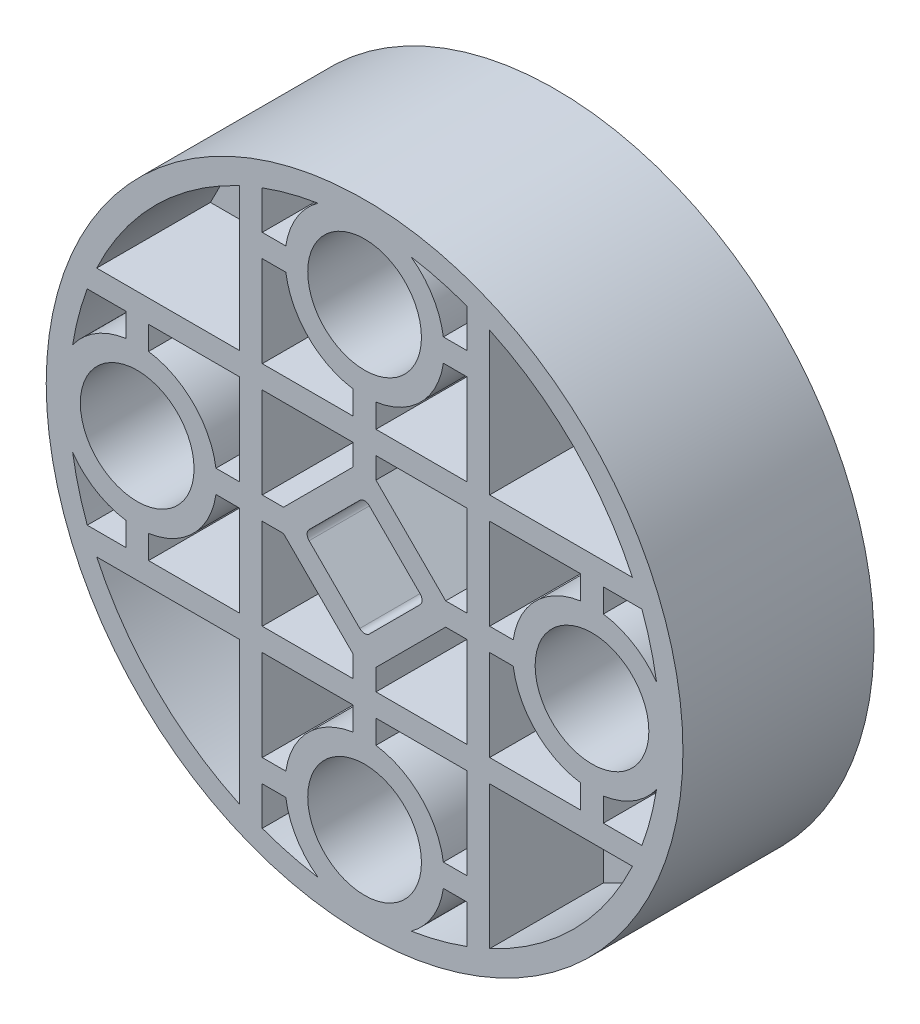
SolidWorks part; units mm, degrees
ref_plane "Front Plane" through (0, 0, 0) normal (0, 0, 1) x (1, 0, 0)
ref_plane "Top Plane" through (0, 0, 0) normal (0, 1, 0) x (1, 0, 0)
ref_plane "Right Plane" through (0, 0, 0) normal (1, 0, 0) x (0, 0, -1)
sketch "Sketch1" plane through (0, 0, 0) normal (0, 0, 1) x (1, 0, 0)
  line L0 (-22.0244, -11.2) -> (5.9756, -11.2) construction
  line L1 (-8.0244, -25.2) -> (-8.0244, 2.8) construction
  circle A0 centre (-8.0244, -11.2) radius 14 construction
  circle A1 centre (-8.0244, -11.2) radius 14
  circle A2 centre (-18.0244, -11.2) radius 2.5 construction
  circle A3 centre (-18.0244, -11.2) radius 2.5
  circle A4 centre (-8.0244, -1.2) radius 2.5 construction
  circle A5 centre (-8.0244, -1.2) radius 2.5
  circle A8 centre (-8.0244, -21.2) radius 2.5 construction
  circle A9 centre (1.9756, -11.2) radius 2.5 construction
  circle A10 centre (-8.0244, -21.2) radius 2.5
  circle A11 centre (1.9756, -11.2) radius 2.5
extrude "Boss-Extrude1" add sketch "Sketch1" along normal up to vertex (9.2 mm away)
sketch "Sketch2" plane through (0, 0, 9.2) normal (0, 0, 1) x (1, 0, 0)
  line L0 (-9.9744, -12.9197) -> (-9.9744, -9.4803)
  line L2 (-6.0744, -12.9197) -> (-6.0744, -9.4803)
  circle A0 centre (-8.0244, -11.2) radius 2.6
  dimension "D1" = 5.2
  dimension "D2" = 3.9
extrude "Cut-Extrude1" cut sketch "Sketch2" against normal through all contours L2 A0 L0
sketch "Sketch3" plane through (0, 0, 9.2) normal (0, 0, 1) x (1, 0, 0)
  line L0 (-12.5244, -23.2) -> (-12.5244, -23.3963)
  line L1 (-20.0244, -6.7) -> (-20.2207, -6.7)
  line L2 (-13.0244, 0.8) -> (-13.0244, -23.2) construction
  line L3 (-3.0244, -23.2) -> (-3.0244, 0.8) construction
  line L4 (-4.0744, -13.5574) -> (-4.0744, -8.8426)
  line L5 (-11.9744, -8.8426) -> (-11.9744, -13.5574)
  line L6 (-4.0744, -13.5574) -> (-4.0744, -8.8426)
  line L7 (-11.9744, -8.8426) -> (-11.9744, -13.5574)
  line L8 (-8.0244, -11.2) -> (-8.0244, 2.8) construction
  line L9 (-13.5244, 0.5792) -> (-13.5244, -22.9792)
  line L10 (-12.5244, 0.9963) -> (-12.5244, -23.2)
  line L11 (-2.5244, -22.9792) -> (-2.5244, 0.5792)
  line L12 (-3.5244, -23.3963) -> (-3.5244, 0.9963)
  line L13 (-3.5244, -23.2) -> (-3.5244, 0.8) construction
  line L14 (-2.5244, -23.2) -> (-2.5244, 0.8) construction
  line L15 (-12.5244, 0.8) -> (-12.5244, -23.2) construction
  line L16 (-13.5244, 0.8) -> (-13.5244, -23.2) construction
  line L17 (4.1719, -6.7) -> (-20.0244, -6.7)
  line L18 (3.7548, -5.7) -> (-19.8036, -5.7)
  line L19 (-20.2207, -15.7) -> (4.1719, -15.7)
  line L20 (-19.8036, -16.7) -> (3.7548, -16.7)
  line L21 (-8.0244, -11.2) -> (-12.5244, -23.2) construction
  line L22 (-8.0244, -11.2) -> (-20.0244, -6.7) construction
  circle A2 centre (-18.0244, -11.2) radius 3.5
  circle A3 centre (-18.0244, -11.2) radius 3.5
  circle A19 centre (-8.0244, -21.2) radius 3.5
  circle A20 centre (-8.0244, -21.2) radius 3.5
  circle A22 centre (1.9756, -11.2) radius 3.5
  circle A23 centre (1.9756, -11.2) radius 3.5
  circle A25 centre (-8.0244, -1.2) radius 3.5
  circle A26 centre (-8.0244, -1.2) radius 3.5
  circle A28 centre (-8.0244, -11.2) radius 13
  circle A29 centre (-8.0244, -11.2) radius 13
  arc A34 (-11.9744, -13.5574) -> (-4.0744, -13.5574) centre (-8.0244, -11.2) ccw
  arc A35 (-4.0744, -8.8426) -> (-11.9744, -8.8426) centre (-8.0244, -11.2) ccw
  arc A36 (-11.9744, -13.5574) -> (-4.0744, -13.5574) centre (-8.0244, -11.2) ccw
  arc A37 (-4.0744, -8.8426) -> (-11.9744, -8.8426) centre (-8.0244, -11.2) ccw
  dimension "D7" = 5
  dimension "D8" = 5
  dimension "D13" = 2
  dimension "D14" = 90
  dimension "D1" = 1
  dimension "D2" = 1
  dimension "D3" = 1
  dimension "D4" = 1
  dimension "D5" = 1
  dimension "D6" = 2
  dimension "D9" = 0.5
  dimension "D10" = 0.5
  dimension "D11" = 0.5
  dimension "D12" = 0.5
extrude "Cut-Extrude2" cut sketch "Sketch3" against normal blind 5 contours L9 A29 L18 | L12 A29 A26 L10 L18 | L1 A29 A3 L19 L9 L17 | A37 L17 L10 L19 A36 L7 | A37 L6 A36 L19 L12 L17 | A23 A29 L17 L11 L19 | L18 A29 L11 | L11 A29 L20 | L0 A29 A20 L12 L20 L10 | L20 A29 L9
sketch "Sketch4" plane through (0, 0, 0) normal (0, 0, -1) x (-1, 0, 0)
  circle A2 centre (8.0244, -11.2) radius 13
  circle A3 centre (8.0244, -11.2) radius 13
  dimension "D1" = 1
extrude "Cut-Extrude3" cut sketch "Sketch4" against normal blind 0.8
sketch "Sketch5" plane through (0, 0, 0.8) normal (0, 0, -1) x (-1, 0, 0)
  line L0 (8.0244, 2.8) -> (8.0244, -25.2) construction
  circle A0 centre (8.0244, -11.2) radius 4.25
  dimension "D1" = 8.5
extrude "Cut-Extrude4" cut sketch "Sketch5" against normal offset from surface (0.7 mm away) 1.5 up to face at (-21.0244, -11.2, 0)
sketch "Sketch6" plane through (0, 0, 0.8) normal (0, 0, -1) x (-1, 0, 0)
  circle A0 centre (8.0244, -11.2) radius 4.25 construction
  circle A1 centre (8.0244, -11.2) radius 4.25
  circle A2 centre (8.0244, -11.2) radius 5.25
  dimension "D1" = 1
extrude "Boss-Extrude2" add sketch "Sketch6" along normal up to surface (0.8 mm away) up to face at (-21.0244, -11.2, 0)
sketch "Sketch7" plane through (0, 0, 0.8) normal (0, 0, -1) x (-1, 0, 0)
  line L0 (7.0705, -15.7) -> (3.5244, -15.7) construction
  line L1 (3.5244, -6.7) -> (7.0705, -6.7) construction
  line L2 (3.5244, -5.7) -> (12.5244, -5.7) construction
  line L3 (12.5244, -16.7) -> (3.5244, -16.7) construction
  line L4 (-3.7548, -5.7) -> (2.5244, -5.7) construction
  line L5 (-4.1719, -6.7) -> (2.5244, -6.7) construction
  line L6 (2.5244, -15.7) -> (-4.1719, -15.7) construction
  line L7 (2.5244, -16.7) -> (-3.7548, -16.7) construction
  line L8 (2.5244, -22.9792) -> (2.5244, -16.7) construction
  line L9 (3.5244, -23.3963) -> (3.5244, -16.7) construction
  line L10 (2.5244, -15.7) -> (2.5244, -6.7) construction
  line L11 (2.5244, -5.7) -> (2.5244, 0.5792) construction
  line L12 (3.5244, -5.7) -> (3.5244, 0.9963) construction
  line L13 (3.5244, -15.7) -> (3.5244, -6.7) construction
  line L14 (12.5244, -16.7) -> (12.5244, -23.3963) construction
  line L15 (12.5244, 0.9963) -> (12.5244, -5.7) construction
  line L16 (12.5244, -6.7) -> (12.5244, -15.7) construction
  line L17 (13.5244, -16.7) -> (13.5244, -22.9792) construction
  line L18 (13.5244, 0.5792) -> (13.5244, -5.7) construction
  line L19 (13.5244, -5.7) -> (19.8036, -5.7) construction
  line L20 (13.5244, -6.7) -> (20.2207, -6.7) construction
  line L21 (13.5244, -6.7) -> (13.5244, -15.7) construction
  line L22 (20.2207, -15.7) -> (13.5244, -15.7) construction
  line L23 (19.8036, -16.7) -> (13.5244, -16.7) construction
  line L24 (12.5244, -15.7) -> (3.5244, -15.7)
  line L25 (3.5244, -6.7) -> (12.5244, -6.7)
  line L26 (3.5244, -5.7) -> (12.5244, -5.7)
  line L27 (12.5244, -16.7) -> (3.5244, -16.7)
  line L28 (-3.7548, -5.7) -> (2.5244, -5.7)
  line L29 (-4.1719, -6.7) -> (2.5244, -6.7)
  line L30 (2.5244, -15.7) -> (-4.1719, -15.7)
  line L31 (2.5244, -16.7) -> (-3.7548, -16.7)
  line L32 (2.5244, -22.9792) -> (2.5244, -16.7)
  line L33 (3.5244, -23.3963) -> (3.5244, -16.7)
  line L34 (2.5244, -15.7) -> (2.5244, -6.7)
  line L35 (2.5244, -5.7) -> (2.5244, 0.5792)
  line L36 (3.5244, -5.7) -> (3.5244, 0.9963)
  line L37 (3.5244, -15.7) -> (3.5244, -6.7)
  line L38 (12.5244, -16.7) -> (12.5244, -23.3963)
  line L39 (12.5244, 0.9963) -> (12.5244, -5.7)
  line L40 (12.5244, -6.7) -> (12.5244, -15.7)
  line L41 (13.5244, -16.7) -> (13.5244, -22.9792)
  line L42 (13.5244, 0.5792) -> (13.5244, -5.7)
  line L43 (13.5244, -5.7) -> (19.8036, -5.7)
  line L44 (13.5244, -6.7) -> (20.2207, -6.7)
  line L45 (13.5244, -6.7) -> (13.5244, -15.7)
  line L46 (20.2207, -15.7) -> (13.5244, -15.7)
  line L47 (19.8036, -16.7) -> (13.5244, -16.7)
  circle A2 centre (18.0244, -11.2) radius 3.5
  circle A3 centre (18.0244, -11.2) radius 3.5
  circle A5 centre (8.0244, -1.2) radius 3.5
  circle A6 centre (8.0244, -1.2) radius 3.5
  circle A8 centre (-1.9756, -11.2) radius 3.5
  circle A9 centre (-1.9756, -11.2) radius 3.5
  circle A10 centre (8.0244, -11.2) radius 13 construction
  circle A11 centre (8.0244, -21.2) radius 3.5
  circle A12 centre (8.0244, -21.2) radius 3.5
  circle A13 centre (8.0244, -11.2) radius 13
  circle A14 centre (8.0244, -11.2) radius 5.25 construction
  circle A15 centre (8.0244, -11.2) radius 5.25
  circle A17 centre (8.0244, -11.2) radius 14
  circle A18 centre (8.0244, -11.2) radius 14
  circle M6 centre (8.0244, -11.2) radius 13
  circle M11 centre (8.0244, -11.2) radius 5.25
  dimension "D1" = 1
  dimension "D2" = 1
  dimension "D3" = 1
  dimension "D4" = 1
  dimension "D5" = 0
extrude "Cut-Extrude5" cut sketch "Sketch7" against normal offset from surface (2.4 mm away) 1 contours L28 L35 M6 | A9 L30 L34 L29 M6 | L32 L31 M6 | A12 L38 L27 L33 M6 | A6 L36 L26 L39 M6 | L42 L43 M6 | A3 L44 L45 L46 M6 | L47 L41 M6 | L40 L24 M11 | L40 L25 M11 | L37 L25 M11 | L37 L24 M11 up to face at (-0.2471, -18.9773, 4.2)
chamfer "Chamfer1" distance 0.6 angle 45 4 edges at (-6.0744, -11.2, 1.5) (-8.0244, -8.6, 1.5) (-8.0244, -13.8, 1.5) (-9.9744, -11.2, 1.5)
sketch "Sketch8" plane through (0, 0, 9.2) normal (0, 0, 1) x (1, 0, 0)
  line L0 (-11.9744, -8.8426) -> (-11.9744, -13.5574) construction
  line L1 (-11.9744, -8.8426) -> (-11.9744, -13.5574)
  line L2 (-4.0744, -13.5574) -> (-4.0744, -8.8426) construction
  line L3 (-4.0744, -13.5574) -> (-4.0744, -8.8426)
  line L4 (-8.0244, -7.1341) -> (-12.0903, -11.2)
  line L5 (-3.9586, -11.2) -> (-8.0244, -7.1341)
  line L6 (-8.0244, -15.2659) -> (-3.9586, -11.2)
  line L7 (-12.0903, -11.2) -> (-8.0244, -15.2659)
  line L8 (-8.0244, -7.1341) -> (-12.0903, -11.2)
  line L9 (-3.9586, -11.2) -> (-8.0244, -7.1341)
  line L10 (-8.0244, -15.2659) -> (-3.9586, -11.2)
  line L11 (-12.0903, -11.2) -> (-8.0244, -15.2659)
  line L12 (-8.0244, -13.8517) -> (-5.3728, -11.2)
  line L13 (-10.6761, -11.2) -> (-8.0244, -13.8517)
  line L14 (-8.0244, -8.5483) -> (-10.6761, -11.2)
  line L15 (-5.3728, -11.2) -> (-8.0244, -8.5483)
  line L16 (-8.0244, -13.8517) -> (-5.3728, -11.2)
  line L17 (-10.6761, -11.2) -> (-8.0244, -13.8517)
  line L18 (-8.0244, -8.5483) -> (-10.6761, -11.2)
  line L19 (-5.3728, -11.2) -> (-8.0244, -8.5483)
  line L20 (-3.5244, -6.7) -> (-12.5244, -6.7)
  line L21 (-3.5244, -15.7) -> (-3.5244, -6.7)
  line L22 (-12.5244, -15.7) -> (-3.5244, -15.7)
  line L23 (-12.5244, -6.7) -> (-12.5244, -15.7)
  line L24 (-3.5244, -6.7) -> (-12.5244, -6.7)
  line L25 (-3.5244, -15.7) -> (-3.5244, -6.7)
  line L26 (-12.5244, -15.7) -> (-3.5244, -15.7)
  line L27 (-12.5244, -6.7) -> (-12.5244, -15.7)
  dimension "D1" = 0
  dimension "D2" = 0
  dimension "D3" = 0
extrude "Cut-Extrude6" cut sketch "Sketch8" against normal up to surface (5 mm away)
sketch "Sketch9" plane through (0, 0, 9.2) normal (0, 0, 1) x (1, 0, 0)
  line L0 (-4.0744, -13.5574) -> (-4.0744, -8.8426) construction
  line L1 (-11.9744, -8.8426) -> (-11.9744, -13.5574) construction
  line L2 (-4.0744, -13.5574) -> (-4.0744, -8.8426)
  line L3 (-11.9744, -8.8426) -> (-11.9744, -13.5574)
  line L4 (-3.5244, -6.7) -> (-12.5244, -6.7)
  line L5 (-12.5244, -6.7) -> (-12.5244, -15.7)
  line L6 (-12.5244, -15.7) -> (-3.5244, -15.7)
  line L7 (-3.5244, -15.7) -> (-3.5244, -6.7)
  line L8 (-3.5244, -6.7) -> (-12.5244, -6.7)
  line L9 (-12.5244, -6.7) -> (-12.5244, -15.7)
  line L10 (-12.5244, -15.7) -> (-3.5244, -15.7)
  line L11 (-3.5244, -15.7) -> (-3.5244, -6.7)
  line L12 (-8.0244, -13.8517) -> (-5.3728, -11.2)
  line L13 (-5.3728, -11.2) -> (-8.0244, -8.5483)
  line L14 (-8.0244, -8.5483) -> (-10.6761, -11.2)
  line L15 (-10.6761, -11.2) -> (-8.0244, -13.8517)
  line L16 (-8.0244, -13.8517) -> (-5.3728, -11.2)
  line L17 (-5.3728, -11.2) -> (-8.0244, -8.5483)
  line L18 (-8.0244, -8.5483) -> (-10.6761, -11.2)
  line L19 (-10.6761, -11.2) -> (-8.0244, -13.8517)
  line L20 (-8.0244, -7.1341) -> (-12.0903, -11.2)
  line L21 (-12.0903, -11.2) -> (-8.0244, -15.2659)
  line L22 (-8.0244, -15.2659) -> (-3.9586, -11.2)
  line L23 (-3.9586, -11.2) -> (-8.0244, -7.1341)
  line L24 (-8.0244, -7.1341) -> (-12.0903, -11.2)
  line L25 (-12.0903, -11.2) -> (-8.0244, -15.2659)
  line L26 (-8.0244, -15.2659) -> (-3.9586, -11.2)
  line L27 (-3.9586, -11.2) -> (-8.0244, -7.1341)
  line M18 (-11.9744, -11.0841) -> (-11.9744, -11.3159)
  line M21 (-4.0744, -11.3159) -> (-4.0744, -11.0841)
  dimension "D1" = 0
  dimension "D2" = 0
  dimension "D3" = 0
extrude "Boss-Extrude3" add sketch "Sketch9" against normal up to surface (5 mm away) contours L24 L25 M18 | L26 L27 M21 up to face at (-8.0244, -11.2, 4.2)
sketch "Sketch10" plane through (0, 0, 9.2) normal (0, 0, 1) x (1, 0, 0)
  line L4 (-8.0244, -7.1341) -> (-12.0903, -11.2)
  line L5 (-12.0903, -11.2) -> (-8.0244, -15.2659)
  line L6 (-8.0244, -15.2659) -> (-3.9586, -11.2)
  line L7 (-3.9586, -11.2) -> (-8.0244, -7.1341)
  line L8 (-8.0244, -7.1341) -> (-12.0903, -11.2)
  line L9 (-12.0903, -11.2) -> (-8.0244, -15.2659)
  line L10 (-8.0244, -15.2659) -> (-3.9586, -11.2)
  line L11 (-3.9586, -11.2) -> (-8.0244, -7.1341)
  dimension "D1" = 0
extrude "Boss-Extrude4" add sketch "Sketch10" against normal up to surface (0.2 mm away)
sketch "Sketch11" plane through (0, 0, 9.2) normal (0, 0, 1) x (1, 0, 0)
  line L0 (-11.9744, -8.8426) -> (-11.9744, -13.5574) construction
  line L1 (-4.0744, -13.5574) -> (-4.0744, -8.8426) construction
  line L2 (-11.9744, -8.8426) -> (-11.9744, -13.5574)
  line L3 (-4.0744, -13.5574) -> (-4.0744, -8.8426)
  line L4 (-8.0244, -7.1341) -> (-12.0903, -11.2)
  line L5 (-12.0903, -11.2) -> (-8.0244, -15.2659)
  line L6 (-8.0244, -15.2659) -> (-3.9586, -11.2)
  line L7 (-3.9586, -11.2) -> (-8.0244, -7.1341)
  line L8 (-8.0244, -7.1341) -> (-12.0903, -11.2)
  line L9 (-12.0903, -11.2) -> (-8.0244, -15.2659)
  line L10 (-8.0244, -15.2659) -> (-3.9586, -11.2)
  line L11 (-3.9586, -11.2) -> (-8.0244, -7.1341)
  line L12 (-8.0244, -13.8517) -> (-5.3728, -11.2)
  line L13 (-5.3728, -11.2) -> (-8.0244, -8.5483)
  line L14 (-8.0244, -8.5483) -> (-10.6761, -11.2)
  line L15 (-10.6761, -11.2) -> (-8.0244, -13.8517)
  line L16 (-8.0244, -13.8517) -> (-5.3728, -11.2)
  line L17 (-5.3728, -11.2) -> (-8.0244, -8.5483)
  line L18 (-8.0244, -8.5483) -> (-10.6761, -11.2)
  line L19 (-10.6761, -11.2) -> (-8.0244, -13.8517)
  line L20 (-3.5244, -6.7) -> (-12.5244, -6.7)
  line L21 (-12.5244, -6.7) -> (-12.5244, -15.7)
  line L22 (-12.5244, -15.7) -> (-3.5244, -15.7)
  line L23 (-3.5244, -15.7) -> (-3.5244, -6.7)
  line L24 (-3.5244, -6.7) -> (-12.5244, -6.7)
  line L25 (-12.5244, -6.7) -> (-12.5244, -15.7)
  line L26 (-12.5244, -15.7) -> (-3.5244, -15.7)
  line L27 (-3.5244, -15.7) -> (-3.5244, -6.7)
  dimension "D1" = 0
  dimension "D2" = 0
  dimension "D3" = 0
extrude "Cut-Extrude7" cut sketch "Sketch11" against normal up to surface (0.2 mm away) contours L18 L19 L16 L17 up to face at (-8.0244, -11.2, 9)
fillet "Fillet1" [suppressed] radius 0.2
sketch "Sketch12" plane through (0, 0, 9.2) normal (0, 0, 1) x (1, 0, 0)
  line L4 (-12.0903, -11.2) -> (-8.0244, -15.2659)
  line L5 (-8.0244, -7.1341) -> (-12.0903, -11.2)
  line L6 (-3.9586, -11.2) -> (-8.0244, -7.1341)
  line L7 (-8.0244, -15.2659) -> (-3.9586, -11.2)
  line L8 (-12.0903, -11.2) -> (-8.0244, -15.2659)
  line L9 (-8.0244, -7.1341) -> (-12.0903, -11.2)
  line L10 (-3.9586, -11.2) -> (-8.0244, -7.1341)
  line L11 (-8.0244, -15.2659) -> (-3.9586, -11.2)
  line L12 (-13.1509, -11.2) -> (-8.0244, -16.3265)
  line L13 (-8.0244, -6.0735) -> (-13.1509, -11.2)
  line L14 (-2.8979, -11.2) -> (-8.0244, -6.0735)
  line L15 (-8.0244, -16.3265) -> (-2.8979, -11.2)
  line L16 (-13.1509, -11.2) -> (-8.0244, -16.3265)
  line L17 (-8.0244, -6.0735) -> (-13.1509, -11.2)
  line L18 (-2.8979, -11.2) -> (-8.0244, -6.0735)
  line L19 (-8.0244, -16.3265) -> (-2.8979, -11.2)
  dimension "D1" = 0
  dimension "D2" = 0
extrude "Boss-Extrude5" [suppressed] add sketch "Sketch12" against normal up to surface (5 mm away)
sketch "Sketch13" plane through (0, 0, 9.2) normal (0, 0, 1) x (1, 0, 0)
  line L0 (-20.2207, -15.7) -> (-13.5244, -15.7) construction
  line L1 (-13.5244, -6.7) -> (-13.5244, -15.7) construction
  line L2 (-13.5244, -6.7) -> (-20.2207, -6.7) construction
  line L3 (-12.5244, 0.9963) -> (-12.5244, -5.7) construction
  line L4 (-3.5244, -5.7) -> (-12.5244, -5.7) construction
  line L5 (-3.5244, -5.7) -> (-3.5244, 0.9963) construction
  line L6 (-3.5244, -1.7) -> (-12.5244, -1.7) construction
  line L7 (-8.5244, -1.2) -> (-8.5244, -21.2) construction
  line L8 (-7.5244, -1.2) -> (-7.5244, -21.2) construction
  line L9 (-3.5244, -0.7) -> (-12.5244, -0.7) construction
  line L10 (-3.5244, -20.7) -> (-12.5244, -20.7) construction
  line L11 (-3.5244, -21.7) -> (-12.5244, -21.7) construction
  line L12 (-3.5244, -16.7) -> (-3.5244, -23.3963) construction
  line L13 (-12.5244, -16.7) -> (-3.5244, -16.7) construction
  line L14 (-12.5244, -23.3963) -> (-12.5244, -16.7) construction
  line L15 (-2.5244, -6.7) -> (4.1719, -6.7) construction
  line L16 (-2.5244, -15.7) -> (-2.5244, -6.7) construction
  line L17 (-18.0244, -11.7) -> (1.9756, -11.7) construction
  line L18 (-18.0244, -10.7) -> (1.9756, -10.7) construction
  line L19 (1.4756, -6.7) -> (1.4756, -15.7) construction
  line L20 (2.4756, -6.7) -> (2.4756, -15.7) construction
  line L21 (4.1719, -15.7) -> (-2.5244, -15.7) construction
  line L22 (-18.5244, -6.7) -> (-18.5244, -15.7) construction
  line L23 (-17.5244, -6.7) -> (-17.5244, -15.7) construction
  line L24 (-20.2207, -15.7) -> (-13.5244, -15.7)
  line L25 (-13.5244, -6.7) -> (-13.5244, -15.7)
  line L26 (-13.5244, -6.7) -> (-20.2207, -6.7)
  line L27 (-12.5244, 0.9963) -> (-12.5244, -5.7)
  line L28 (-3.5244, -5.7) -> (-12.5244, -5.7)
  line L29 (-3.5244, -5.7) -> (-3.5244, 0.9963)
  line L30 (-3.5244, -1.7) -> (-12.5244, -1.7)
  line L31 (-8.5244, -1.2) -> (-8.5244, -21.2)
  line L32 (-7.5244, -1.2) -> (-7.5244, -21.2)
  line L33 (-3.5244, -0.7) -> (-12.5244, -0.7)
  line L34 (-3.5244, -20.7) -> (-12.5244, -20.7)
  line L35 (-3.5244, -21.7) -> (-12.5244, -21.7)
  line L36 (-3.5244, -16.7) -> (-3.5244, -23.3963)
  line L37 (-12.5244, -16.7) -> (-3.5244, -16.7)
  line L38 (-12.5244, -23.3963) -> (-12.5244, -16.7)
  line L39 (-2.5244, -6.7) -> (4.1719, -6.7)
  line L40 (-2.5244, -15.7) -> (-2.5244, -6.7)
  line L41 (-18.0244, -11.7) -> (1.9756, -11.7)
  line L42 (-18.0244, -10.7) -> (1.9756, -10.7)
  line L43 (1.4756, -6.7) -> (1.4756, -15.7)
  line L44 (2.4756, -6.7) -> (2.4756, -15.7)
  line L45 (4.1719, -15.7) -> (-2.5244, -15.7)
  line L46 (-18.5244, -6.7) -> (-18.5244, -15.7)
  line L47 (-17.5244, -6.7) -> (-17.5244, -15.7)
  line L48 (-12.5244, -6.7) -> (-12.5244, -15.7) construction
  line L49 (-3.5244, -15.7) -> (-3.5244, -6.7) construction
  line L50 (-8.0244, -15.2659) -> (-3.9586, -11.2) construction
  line L51 (-8.0244, -15.2659) -> (-12.0903, -11.2) construction
  line L52 (-12.0903, -11.2) -> (-8.0244, -7.1341) construction
  line L53 (-8.0244, -7.1341) -> (-3.9586, -11.2) construction
  line L54 (-12.5244, -6.7) -> (-12.5244, -15.7)
  line L55 (-3.5244, -15.7) -> (-3.5244, -6.7)
  line L56 (-8.0244, -15.2659) -> (-3.9586, -11.2)
  line L57 (-8.0244, -15.2659) -> (-12.0903, -11.2)
  line L58 (-12.0903, -11.2) -> (-8.0244, -7.1341)
  line L59 (-8.0244, -7.1341) -> (-3.9586, -11.2)
  arc A0 (-5.9754, -24.0375) -> (-10.0735, -24.0375) centre (-8.0244, -21.2) ccw construction
  arc A1 (4.8131, -9.151) -> (4.8131, -13.249) centre (1.9756, -11.2) ccw construction
  arc A2 (-20.8619, -13.249) -> (-20.8619, -9.151) centre (-18.0244, -11.2) ccw construction
  arc A3 (-10.0735, 1.6375) -> (-5.9754, 1.6375) centre (-8.0244, -1.2) ccw construction
  arc A4 (-5.9754, -24.0375) -> (-10.0735, -24.0375) centre (-8.0244, -21.2) ccw
  arc A5 (4.8131, -9.151) -> (4.8131, -13.249) centre (1.9756, -11.2) ccw
  arc A6 (-20.8619, -13.249) -> (-20.8619, -9.151) centre (-18.0244, -11.2) ccw
  arc A7 (-10.0735, 1.6375) -> (-5.9754, 1.6375) centre (-8.0244, -1.2) ccw
  line M61 (-12.5244, -6.7) -> (-3.5244, -6.7)
  line M62 (-3.5244, -6.7) -> (-3.5244, -15.7)
  line M63 (-3.5244, -15.7) -> (-12.5244, -15.7)
  line M64 (-12.5244, -15.7) -> (-12.5244, -6.7)
extrude "Boss-Extrude6" add sketch "Sketch13" against normal up to surface (5 mm away) contours A4 L34 L38 L35 | A4 L32 L37 L31 | A4 L35 L36 L34 | A5 L43 L45 L44 | A5 L42 L40 L41 | A5 L44 L39 L43 | A7 L30 L29 L33 | A7 L31 L28 L32 | A7 L33 L27 L30 | A6 L41 L25 L42 | A6 L47 L26 L46 | A6 L46 L24 L47 | L57 L58 L42 L41 M64 | L42 L59 L56 L41 M62 | L56 L57 L31 L32 M63 | L58 L59 L32 L31 M61 up to face at (-8.0244, -20.3416, 4.2)
sketch "Sketch14" plane through (0, 0, 0.8) normal (0, 0, -1) x (-1, 0, 0)
  circle A0 centre (8.0244, -11.2) radius 18.4031
extrude "Cut-Extrude8" cut sketch "Sketch14" along normal blind 14
sketch "Sketch15" plane through (0, 0, 0.8) normal (0, 0, -1) x (-1, 0, 0)
  line L1 (3.5244, -6.7) -> (12.5244, -6.7)
  line L2 (3.5244, -6.7) -> (3.5244, -15.7)
  line L3 (3.5244, -15.7) -> (12.5244, -15.7)
  line L4 (12.5244, -6.7) -> (12.5244, -15.7)
extrude "Cut-Extrude9" cut sketch "Sketch15" against normal up to surface (2.4 mm away) up to face at (1.1172, -11.2, 3.2)
sketch "Sketch18" plane through (0, 0, 9.2) normal (0, 0, 1) x (1, 0, 0)
  line L5 (-8.0244, -8.5483) -> (-10.6761, -11.2)
  line L6 (-5.3728, -11.2) -> (-8.0244, -8.5483)
  line L7 (-8.0244, -13.8517) -> (-5.3728, -11.2)
  line L8 (-10.6761, -11.2) -> (-8.0244, -13.8517)
  line L9 (-8.0244, -8.5483) -> (-10.6761, -11.2)
  line L10 (-5.3728, -11.2) -> (-8.0244, -8.5483)
  line L11 (-8.0244, -13.8517) -> (-5.3728, -11.2)
  line L12 (-10.6761, -11.2) -> (-8.0244, -13.8517)
  dimension "D1" = 0
extrude "Cut-Extrude10" cut sketch "Sketch18" against normal through all
sketch "Sketch19" plane through (0, 0, 3.2) normal (0, 0, -1) x (-1, 0, 0)
  line L1 (9.9744, -10.4983) -> (8.0766, -8.6005) construction
  line L2 (6.0744, -10.4983) -> (7.9722, -8.6005)
  line L3 (6.0744, -9.4803) -> (6.0744, -10.4983)
  line L4 (6.0744, -10.4983) -> (7.9722, -8.6005)
  line L5 (6.0744, -9.4803) -> (6.0744, -10.4983)
  line L6 (8.0766, -13.7995) -> (9.9744, -11.9017) construction
  line L7 (7.9722, -13.7995) -> (6.0744, -11.9017)
  line L8 (6.0744, -11.9017) -> (6.0744, -12.9197)
  line L9 (7.9722, -13.7995) -> (6.0744, -11.9017)
  line L10 (6.0744, -11.9017) -> (6.0744, -12.9197)
  line L11 (9.9744, -10.4983) -> (8.0766, -8.6005)
  line L12 (8.0766, -13.7995) -> (9.9744, -11.9017)
  line L16 (10.6761, -11.2) -> (9.9744, -10.4983)
  line L17 (9.9744, -11.9017) -> (10.6761, -11.2)
  line L18 (9.9744, -12.9197) -> (9.9744, -11.9017)
  line L19 (8.0244, -13.8517) -> (8.0766, -13.7995)
  line L20 (7.9722, -13.7995) -> (8.0244, -13.8517)
  line L21 (6.0744, -11.9017) -> (6.0744, -12.9197)
  line L22 (5.3728, -11.2) -> (6.0744, -11.9017)
  line L23 (6.0744, -10.4983) -> (5.3728, -11.2)
  line L24 (6.0744, -9.4803) -> (6.0744, -10.4983)
  line L25 (8.0244, -8.5483) -> (7.9722, -8.6005)
  line L26 (8.0766, -8.6005) -> (8.0244, -8.5483)
  line L27 (9.9744, -10.4983) -> (9.9744, -9.4803)
  line L28 (10.6761, -11.2) -> (9.9744, -10.4983)
  line L29 (9.9744, -11.9017) -> (10.6761, -11.2)
  line L30 (9.9744, -12.9197) -> (9.9744, -11.9017)
  line L31 (8.0244, -13.8517) -> (8.0766, -13.7995)
  line L32 (7.9722, -13.7995) -> (8.0244, -13.8517)
  line L33 (6.0744, -11.9017) -> (6.0744, -12.9197)
  line L34 (5.3728, -11.2) -> (6.0744, -11.9017)
  line L35 (6.0744, -10.4983) -> (5.3728, -11.2)
  line L36 (6.0744, -9.4803) -> (6.0744, -10.4983)
  line L37 (8.0244, -8.5483) -> (7.9722, -8.6005)
  line L38 (8.0766, -8.6005) -> (8.0244, -8.5483)
  line L39 (9.9744, -10.4983) -> (9.9744, -9.4803)
  arc A1 (7.9722, -8.6005) -> (6.0744, -9.4803) centre (8.0244, -11.2) ccw
  arc A2 (7.9722, -8.6005) -> (6.0744, -9.4803) centre (8.0244, -11.2) ccw
  arc A4 (6.0744, -12.9197) -> (7.9722, -13.7995) centre (8.0244, -11.2) ccw
  arc A5 (6.0744, -12.9197) -> (7.9722, -13.7995) centre (8.0244, -11.2) ccw
  arc A7 (8.0766, -13.7995) -> (9.9744, -12.9197) centre (8.0244, -11.2) ccw
  arc A8 (6.0744, -12.9197) -> (7.9722, -13.7995) centre (8.0244, -11.2) ccw
  arc A9 (7.9722, -8.6005) -> (6.0744, -9.4803) centre (8.0244, -11.2) ccw
  arc A10 (9.9744, -9.4803) -> (8.0766, -8.6005) centre (8.0244, -11.2) ccw
  arc A11 (8.0766, -13.7995) -> (9.9744, -12.9197) centre (8.0244, -11.2) ccw
  arc A12 (6.0744, -12.9197) -> (7.9722, -13.7995) centre (8.0244, -11.2) ccw
  arc A13 (7.9722, -8.6005) -> (6.0744, -9.4803) centre (8.0244, -11.2) ccw
  arc A14 (9.9744, -9.4803) -> (8.0766, -8.6005) centre (8.0244, -11.2) ccw
  line M29 (9.9744, -11.9017) -> (9.9744, -12.9197)
  arc M30 (9.9744, -12.9197) -> (8.0766, -13.7995) centre (8.0244, -11.2) cw
  arc M33 (7.9722, -13.7995) -> (6.0744, -12.9197) centre (8.0244, -11.2) cw
  line M34 (6.0744, -12.9197) -> (6.0744, -11.9017)
  line M37 (6.0744, -10.4983) -> (6.0744, -9.4803)
  arc M38 (6.0744, -9.4803) -> (7.9722, -8.6005) centre (8.0244, -11.2) cw
  arc M41 (8.0766, -8.6005) -> (9.9744, -9.4803) centre (8.0244, -11.2) cw
  line M42 (9.9744, -9.4803) -> (9.9744, -10.4983)
  dimension "D1" = 0
  dimension "D2" = 0
  dimension "D3" = 0
extrude "Boss-Extrude7" add sketch "Sketch19" against normal up to surface (5.8 mm away) contours L4 M37 M38 | L11 M42 M41 | L9 M33 M34 | L12 M30 M29 up to face at (-6.6762, -12.94, 9)
sketch "Sketch20" plane through (0, 0, 3.2) normal (0, 0, -1) x (-1, 0, 0)
  line L0 (3.5244, -15.7) -> (3.5244, -6.7) construction
  line L1 (12.5244, -6.7) -> (12.5244, -15.7) construction
  line L2 (8.5244, -1.2) -> (8.5244, -21.2) construction
  line L3 (3.5244, -1.7) -> (12.5244, -1.7) construction
  line L4 (12.0903, -11.2) -> (8.0244, -7.1341)
  line L5 (8.0244, -7.1341) -> (3.9586, -11.2)
  line L6 (3.9586, -11.2) -> (8.0244, -15.2659)
  line L7 (8.0244, -15.2659) -> (12.0903, -11.2)
  line L8 (12.0903, -11.2) -> (8.0244, -7.1341)
  line L9 (8.0244, -7.1341) -> (3.9586, -11.2)
  line L10 (3.9586, -11.2) -> (8.0244, -15.2659)
  line L11 (8.0244, -15.2659) -> (12.0903, -11.2)
  line L12 (12.5244, 0.9963) -> (12.5244, -5.7) construction
  line L13 (3.5244, -5.7) -> (12.5244, -5.7) construction
  line L14 (3.5244, -5.7) -> (3.5244, 0.9963) construction
  line L15 (20.2207, -15.7) -> (13.5244, -15.7) construction
  line L16 (13.5244, -6.7) -> (13.5244, -15.7) construction
  line L17 (13.5244, -6.7) -> (20.2207, -6.7) construction
  line L18 (3.5244, -16.7) -> (3.5244, -23.3963) construction
  line L19 (12.5244, -16.7) -> (3.5244, -16.7) construction
  line L20 (12.5244, -23.3963) -> (12.5244, -16.7) construction
  line L21 (3.5244, -21.7) -> (12.5244, -21.7) construction
  line L22 (3.5244, -20.7) -> (12.5244, -20.7) construction
  line L23 (3.5244, -0.7) -> (12.5244, -0.7) construction
  line L24 (7.5244, -1.2) -> (7.5244, -21.2) construction
  line L25 (18.0244, -11.7) -> (-1.9756, -11.7) construction
  line L26 (2.5244, -6.7) -> (-4.1719, -6.7) construction
  line L27 (2.5244, -15.7) -> (2.5244, -6.7) construction
  line L28 (-4.1719, -15.7) -> (2.5244, -15.7) construction
  line L29 (17.5244, -6.7) -> (17.5244, -15.7) construction
  line L30 (18.5244, -6.7) -> (18.5244, -15.7) construction
  line L31 (-2.4756, -6.7) -> (-2.4756, -15.7) construction
  line L32 (-1.4756, -6.7) -> (-1.4756, -15.7) construction
  line L33 (18.0244, -10.7) -> (-1.9756, -10.7) construction
  line L34 (3.5244, -15.7) -> (3.5244, -6.7)
  line L35 (12.5244, -6.7) -> (12.5244, -15.7)
  line L36 (8.5244, -1.2) -> (8.5244, -21.2)
  line L37 (3.5244, -1.7) -> (12.5244, -1.7)
  line L38 (12.5244, 0.9963) -> (12.5244, -5.7)
  line L39 (3.5244, -5.7) -> (12.5244, -5.7)
  line L40 (3.5244, -5.7) -> (3.5244, 0.9963)
  line L41 (20.2207, -15.7) -> (13.5244, -15.7)
  line L42 (13.5244, -6.7) -> (13.5244, -15.7)
  line L43 (13.5244, -6.7) -> (20.2207, -6.7)
  line L44 (3.5244, -16.7) -> (3.5244, -23.3963)
  line L45 (12.5244, -16.7) -> (3.5244, -16.7)
  line L46 (12.5244, -23.3963) -> (12.5244, -16.7)
  line L47 (3.5244, -21.7) -> (12.5244, -21.7)
  line L48 (3.5244, -20.7) -> (12.5244, -20.7)
  line L49 (3.5244, -0.7) -> (12.5244, -0.7)
  line L50 (7.5244, -1.2) -> (7.5244, -21.2)
  line L51 (18.0244, -11.7) -> (-1.9756, -11.7)
  line L52 (2.5244, -6.7) -> (-4.1719, -6.7)
  line L53 (2.5244, -15.7) -> (2.5244, -6.7)
  line L54 (-4.1719, -15.7) -> (2.5244, -15.7)
  line L55 (17.5244, -6.7) -> (17.5244, -15.7)
  line L56 (18.5244, -6.7) -> (18.5244, -15.7)
  line L57 (-2.4756, -6.7) -> (-2.4756, -15.7)
  line L58 (-1.4756, -6.7) -> (-1.4756, -15.7)
  line L59 (18.0244, -10.7) -> (-1.9756, -10.7)
  line L64 (10.6761, -11.2) -> (8.0244, -8.5483)
  line L65 (8.0244, -13.8517) -> (10.6761, -11.2)
  line L66 (5.3728, -11.2) -> (8.0244, -13.8517)
  line L67 (8.0244, -8.5483) -> (5.3728, -11.2)
  line L68 (10.6761, -11.2) -> (8.0244, -8.5483)
  line L69 (8.0244, -13.8517) -> (10.6761, -11.2)
  line L70 (5.3728, -11.2) -> (8.0244, -13.8517)
  line L71 (8.0244, -8.5483) -> (5.3728, -11.2)
  arc A0 (10.0735, -24.0375) -> (5.9754, -24.0375) centre (8.0244, -21.2) ccw construction
  arc A1 (5.9754, 1.6375) -> (10.0735, 1.6375) centre (8.0244, -1.2) ccw construction
  arc A2 (20.8619, -9.151) -> (20.8619, -13.249) centre (18.0244, -11.2) ccw construction
  arc A3 (-4.8131, -13.249) -> (-4.8131, -9.151) centre (-1.9756, -11.2) ccw construction
  arc A4 (10.0735, -24.0375) -> (5.9754, -24.0375) centre (8.0244, -21.2) ccw
  arc A5 (5.9754, 1.6375) -> (10.0735, 1.6375) centre (8.0244, -1.2) ccw
  arc A6 (20.8619, -9.151) -> (20.8619, -13.249) centre (18.0244, -11.2) ccw
  arc A7 (-4.8131, -13.249) -> (-4.8131, -9.151) centre (-1.9756, -11.2) ccw
  line M9 (8.0244, -8.5483) -> (10.6761, -11.2)
  line M10 (10.6761, -11.2) -> (8.0244, -13.8517)
  line M11 (8.0244, -13.8517) -> (5.3728, -11.2)
  line M12 (5.3728, -11.2) -> (8.0244, -8.5483)
  line M14 (12.5244, -6.7) -> (3.5244, -6.7)
  line M16 (3.5244, -15.7) -> (12.5244, -15.7)
  dimension "D1" = 0
  dimension "D2" = 0
extrude "Boss-Extrude8" add sketch "Sketch20" along normal up to surface (2.4 mm away) contours A7 L58 L52 L57 | A7 L57 L54 L58 | A7 L51 L53 L59 | L9 L59 L34 L51 L10 | L59 L9 L10 L51 M12 M11 | L51 L10 L50 M11 | L50 L10 L11 L36 M11 M10 | L11 L51 L36 M10 | L8 L59 L51 L11 M9 M10 | L59 L8 L36 M9 | L9 L50 L36 L8 M12 M9 | L59 L50 L9 M12 | L35 L59 L8 L11 L51 | L10 L50 L36 L11 M16 | L50 L9 L8 L36 M14 | A5 L50 L39 L36 | A5 L37 L38 L49 | A5 L49 L40 L37 | A6 L59 L42 L51 | A6 L56 L43 L55 | A6 L55 L41 L56 | A4 L36 L45 L50 | A4 L47 L46 L48 | A4 L48 L44 L47 up to face at (-8.0244, -11.2, 0.8)
fillet "Fillet2" radius 0.3 4 edges at (-5.3728, -11.2, 5) (-8.0244, -13.8517, 5) (-10.6761, -11.2, 5) (-8.0244, -8.5483, 5)
